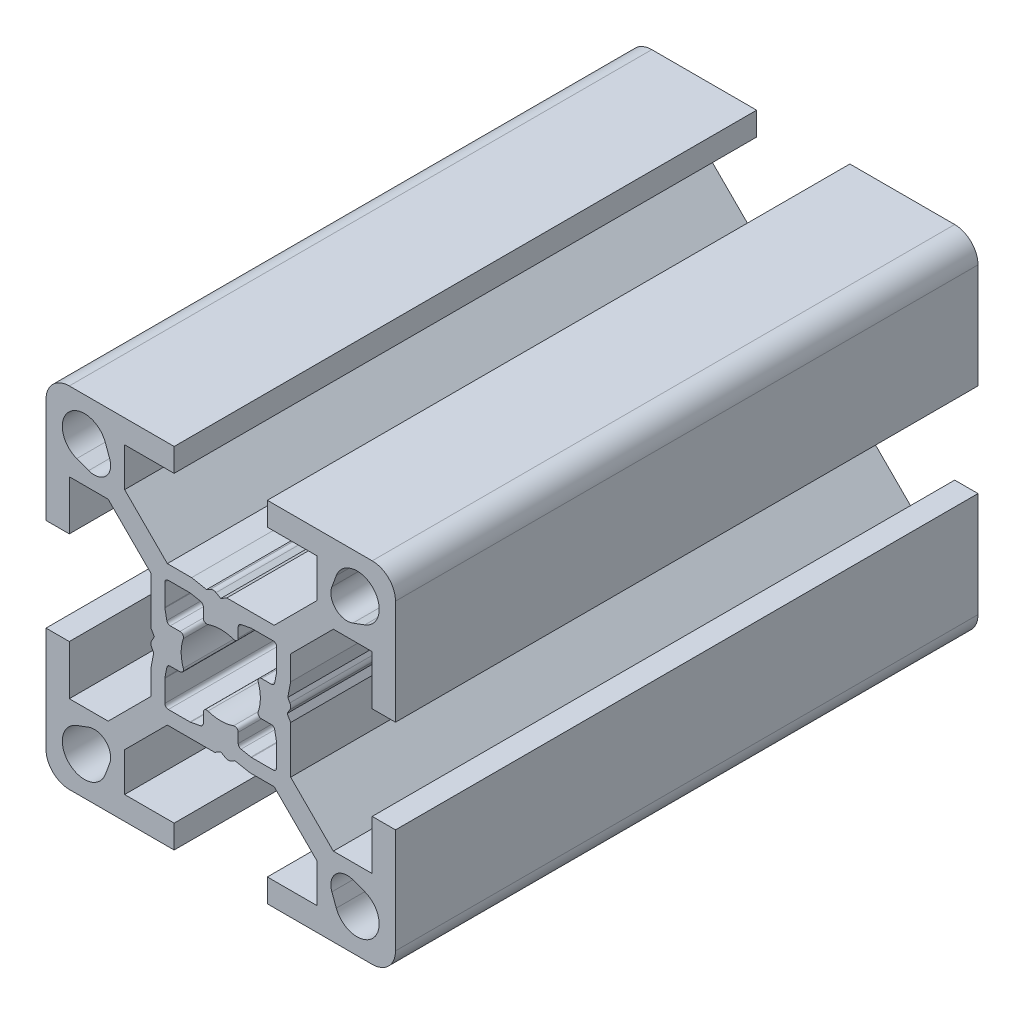
SolidWorks part; units mm, degrees
ref_plane "Front Plane" through (0, 0, 0) normal (0, 0, 1) x (1, 0, 0)
ref_plane "Top Plane" through (0, 0, 0) normal (0, 1, 0) x (1, 0, 0)
ref_plane "Right Plane" through (0, 0, 0) normal (1, 0, 0) x (0, 0, -1)
ref_plane "Plane1" through (0, 0, 0) normal (0, 0, 1) x (1, 0, 0)
sketch "Sketch1" plane through (0, 0, 0) normal (0, 0, 1) x (1, 0, 0)
  line L0 (-15, 4) -> (-13, 4)
  line L1 (-13, 4) -> (-13, 8.25)
  line L2 (-13, 8.25) -> (-9.6642, 8.25)
  line L3 (-9.6642, 8.25) -> (-6, 4.5858)
  line L4 (-6, 4.5858) -> (-6, 0.5196)
  line L5 (-6, 0.5196) -> (-5.7, 0)
  line L6 (-5.7, 0) -> (-5.933, -0.4036)
  line L7 (-5.933, -0.9036) -> (-5.751, -1.2189)
  line L8 (-5.751, -1.2189) -> (-6, -2.5)
  line L9 (-6, -2.5) -> (-6, -4.5858)
  line L10 (-6, -4.5858) -> (-9.6642, -8.25)
  line L11 (-9.6642, -8.25) -> (-13, -8.25)
  line L12 (-13, -8.25) -> (-13, -4)
  line L13 (-13, -4) -> (-15, -4)
  line L14 (-15, -4) -> (-15, -13)
  line L15 (-13, -15) -> (-4, -15)
  line L16 (-4, -15) -> (-4, -13)
  line L17 (-4, -13) -> (-8.25, -13)
  line L18 (-8.25, -13) -> (-8.25, -9.6642)
  line L19 (-8.25, -9.6642) -> (-4.5858, -6)
  line L20 (-4.5858, -6) -> (-0.5196, -6)
  line L21 (-0.5196, -6) -> (0, -5.7)
  line L22 (0, -5.7) -> (0.4036, -5.933)
  line L23 (0.9036, -5.933) -> (1.2189, -5.751)
  line L24 (1.2189, -5.751) -> (2.5, -6)
  line L25 (2.5, -6) -> (4.5858, -6)
  line L26 (4.5858, -6) -> (8.25, -9.6642)
  line L27 (8.25, -9.6642) -> (8.25, -13)
  line L28 (8.25, -13) -> (4, -13)
  line L29 (4, -13) -> (4, -15)
  line L30 (4, -15) -> (13, -15)
  line L31 (15, -13) -> (15, -4)
  line L32 (15, -4) -> (13, -4)
  line L33 (13, -4) -> (13, -8.25)
  line L34 (13, -8.25) -> (9.6642, -8.25)
  line L35 (9.6642, -8.25) -> (6, -4.5858)
  line L36 (6, -4.5858) -> (6, -0.5196)
  line L37 (6, -0.5196) -> (5.7, 0)
  line L38 (5.7, 0) -> (5.933, 0.4036)
  line L39 (5.933, 0.9036) -> (5.751, 1.2189)
  line L40 (5.751, 1.2189) -> (6, 2.5)
  line L41 (6, 2.5) -> (6, 4.5858)
  line L42 (6, 4.5858) -> (9.6642, 8.25)
  line L43 (9.6642, 8.25) -> (13, 8.25)
  line L44 (13, 8.25) -> (13, 4)
  line L45 (13, 4) -> (15, 4)
  line L46 (15, 4) -> (15, 13)
  line L47 (13, 15) -> (4, 15)
  line L48 (4, 15) -> (4, 13)
  line L49 (4, 13) -> (8.25, 13)
  line L50 (8.25, 13) -> (8.25, 9.6642)
  line L51 (8.25, 9.6642) -> (4.5858, 6)
  line L52 (4.5858, 6) -> (0.5196, 6)
  line L53 (0.5196, 6) -> (0, 5.7)
  line L54 (0, 5.7) -> (-0.4036, 5.933)
  line L55 (-0.9036, 5.933) -> (-1.2189, 5.751)
  line L56 (-1.2189, 5.751) -> (-2.5, 6)
  line L57 (-2.5, 6) -> (-4.5858, 6)
  line L58 (-4.5858, 6) -> (-8.25, 9.6642)
  line L59 (-8.25, 9.6642) -> (-8.25, 13)
  line L60 (-8.25, 13) -> (-4, 13)
  line L61 (-4, 13) -> (-4, 15)
  line L62 (-4, 15) -> (-13, 15)
  line L63 (-15, 13) -> (-15, 4)
  line L64 (11.3389, 9.5391) -> (12.3615, 9.9189)
  line L65 (9.9189, 12.3615) -> (9.5391, 11.3389)
  line L66 (9.5391, -11.3389) -> (9.9189, -12.3615)
  line L67 (12.3615, -9.9189) -> (11.3389, -9.5391)
  line L68 (-12.3615, 9.9189) -> (-11.3389, 9.5391)
  line L69 (-9.5391, 11.3389) -> (-9.9189, 12.3615)
  line L70 (-9.9189, -12.3615) -> (-9.5391, -11.3389)
  line L71 (-11.3389, -9.5391) -> (-12.3615, -9.9189)
  arc A0 (-5.933, -0.4036) -> (-5.933, -0.9036) centre (-5.5, -0.6536) ccw
  arc A1 (-15, -13) -> (-13, -15) centre (-13, -13) ccw
  arc A2 (0.4036, -5.933) -> (0.9036, -5.933) centre (0.6536, -5.5) ccw
  arc A3 (13, -15) -> (15, -13) centre (13, -13) ccw
  arc A4 (5.933, 0.4036) -> (5.933, 0.9036) centre (5.5, 0.6536) ccw
  arc A5 (15, 13) -> (13, 15) centre (13, 13) ccw
  arc A6 (-0.4036, 5.933) -> (-0.9036, 5.933) centre (-0.6536, 5.5) ccw
  arc A7 (-13, 15) -> (-15, 13) centre (-13, 13) ccw
  arc A8 (9.5391, 11.3389) -> (11.3389, 9.5391) centre (10.8515, 10.8515) ccw
  arc A9 (12.3615, 9.9189) -> (9.9189, 12.3615) centre (11.7, 11.7) ccw
  arc A10 (11.3389, -9.5391) -> (9.5391, -11.3389) centre (10.8515, -10.8515) ccw
  arc A11 (9.9189, -12.3615) -> (12.3615, -9.9189) centre (11.7, -11.7) ccw
  arc A12 (-9.9189, 12.3615) -> (-12.3615, 9.9189) centre (-11.7, 11.7) ccw
  arc A13 (-11.3389, 9.5391) -> (-9.5391, 11.3389) centre (-10.8515, 10.8515) ccw
  arc A14 (-12.3615, -9.9189) -> (-9.9189, -12.3615) centre (-11.7, -11.7) ccw
  arc A15 (-9.5391, -11.3389) -> (-11.3389, -9.5391) centre (-10.8515, -10.8515) ccw
extrude "Boss-Extrude1" add sketch "Sketch1" against normal blind 50
ref_plane "Plane2" through (0, 0, 0) normal (0, 0, 1) x (1, 0, 0)
sketch "Sketch2" plane through (0, 0, 0) normal (0, 0, 1) x (1, 0, 0)
  line L0 (-4.5, -4.8) -> (-2.6444, -4.8)
  line L1 (-2.5872, -4.7945) -> (-1.7428, -4.6303)
  line L2 (-1.5, -4.3359) -> (-1.5, -3.5)
  line L3 (1.5, -3.5) -> (1.5, -4.3359)
  line L4 (1.7428, -4.6303) -> (2.5872, -4.7945)
  line L5 (2.6444, -4.8) -> (4.5, -4.8)
  line L6 (4.8, -4.5) -> (4.8, -2.6444)
  line L7 (4.7945, -2.5872) -> (4.6303, -1.7428)
  line L8 (4.3359, -1.5) -> (3.5, -1.5)
  line L9 (3.5, 1.5) -> (4.3359, 1.5)
  line L10 (4.6303, 1.7428) -> (4.7945, 2.5872)
  line L11 (4.8, 2.6444) -> (4.8, 4.5)
  line L12 (4.5, 4.8) -> (2.6444, 4.8)
  line L13 (2.5872, 4.7945) -> (1.7428, 4.6303)
  line L14 (1.5, 4.3359) -> (1.5, 3.5)
  line L15 (-1.5, 3.5) -> (-1.5, 4.3359)
  line L16 (-1.7428, 4.6303) -> (-2.5872, 4.7945)
  line L17 (-2.6444, 4.8) -> (-4.5, 4.8)
  line L18 (-4.8, 4.5) -> (-4.8, 2.6444)
  line L19 (-4.7945, 2.5872) -> (-4.6303, 1.7428)
  line L20 (-4.3359, 1.5) -> (-3.5, 1.5)
  line L21 (-3.5, -1.5) -> (-4.3359, -1.5)
  line L22 (-4.6303, -1.7428) -> (-4.7945, -2.5872)
  line L23 (-4.8, -2.6444) -> (-4.8, -4.5)
  arc A0 (-4.8, -4.5) -> (-4.5, -4.8) centre (-4.5, -4.5) ccw
  arc A1 (-2.6444, -4.8) -> (-2.5872, -4.7945) centre (-2.6444, -4.5) ccw
  arc A2 (-1.7428, -4.6303) -> (-1.5, -4.3359) centre (-1.8, -4.3359) ccw
  arc A3 (-1.5, -3.5) -> (-1.1027, -3.2162) centre (-1.2, -3.5) cw
  arc A4 (-1.1027, -3.2162) -> (1.1027, -3.2162) centre (0, 0) ccw
  arc A5 (1.1027, -3.2162) -> (1.5, -3.5) centre (1.2, -3.5) cw
  arc A6 (1.5, -4.3359) -> (1.7428, -4.6303) centre (1.8, -4.3359) ccw
  arc A7 (2.5872, -4.7945) -> (2.6444, -4.8) centre (2.6444, -4.5) ccw
  arc A8 (4.5, -4.8) -> (4.8, -4.5) centre (4.5, -4.5) ccw
  arc A9 (4.8, -2.6444) -> (4.7945, -2.5872) centre (4.5, -2.6444) ccw
  arc A10 (4.6303, -1.7428) -> (4.3359, -1.5) centre (4.3359, -1.8) ccw
  arc A11 (3.5, -1.5) -> (3.2162, -1.1027) centre (3.5, -1.2) cw
  arc A12 (3.2162, -1.1027) -> (3.2162, 1.1027) centre (0, 0) ccw
  arc A13 (3.2162, 1.1027) -> (3.5, 1.5) centre (3.5, 1.2) cw
  arc A14 (4.3359, 1.5) -> (4.6303, 1.7428) centre (4.3359, 1.8) ccw
  arc A15 (4.7945, 2.5872) -> (4.8, 2.6444) centre (4.5, 2.6444) ccw
  arc A16 (4.8, 4.5) -> (4.5, 4.8) centre (4.5, 4.5) ccw
  arc A17 (2.6444, 4.8) -> (2.5872, 4.7945) centre (2.6444, 4.5) ccw
  arc A18 (1.7428, 4.6303) -> (1.5, 4.3359) centre (1.8, 4.3359) ccw
  arc A19 (1.5, 3.5) -> (1.1027, 3.2162) centre (1.2, 3.5) cw
  arc A20 (1.1027, 3.2162) -> (-1.1027, 3.2162) centre (0, 0) ccw
  arc A21 (-1.1027, 3.2162) -> (-1.5, 3.5) centre (-1.2, 3.5) cw
  arc A22 (-1.5, 4.3359) -> (-1.7428, 4.6303) centre (-1.8, 4.3359) ccw
  arc A23 (-2.5872, 4.7945) -> (-2.6444, 4.8) centre (-2.6444, 4.5) ccw
  arc A24 (-4.5, 4.8) -> (-4.8, 4.5) centre (-4.5, 4.5) ccw
  arc A25 (-4.8, 2.6444) -> (-4.7945, 2.5872) centre (-4.5, 2.6444) ccw
  arc A26 (-4.6303, 1.7428) -> (-4.3359, 1.5) centre (-4.3359, 1.8) ccw
  arc A27 (-3.5, 1.5) -> (-3.2162, 1.1027) centre (-3.5, 1.2) cw
  arc A28 (-3.2162, 1.1027) -> (-3.2162, -1.1027) centre (0, 0) ccw
  arc A29 (-3.2162, -1.1027) -> (-3.5, -1.5) centre (-3.5, -1.2) cw
  arc A30 (-4.3359, -1.5) -> (-4.6303, -1.7428) centre (-4.3359, -1.8) ccw
  arc A31 (-4.7945, -2.5872) -> (-4.8, -2.6444) centre (-4.5, -2.6444) ccw
extrude "Cut-Extrude1" cut sketch "Sketch2" against normal blind 50
